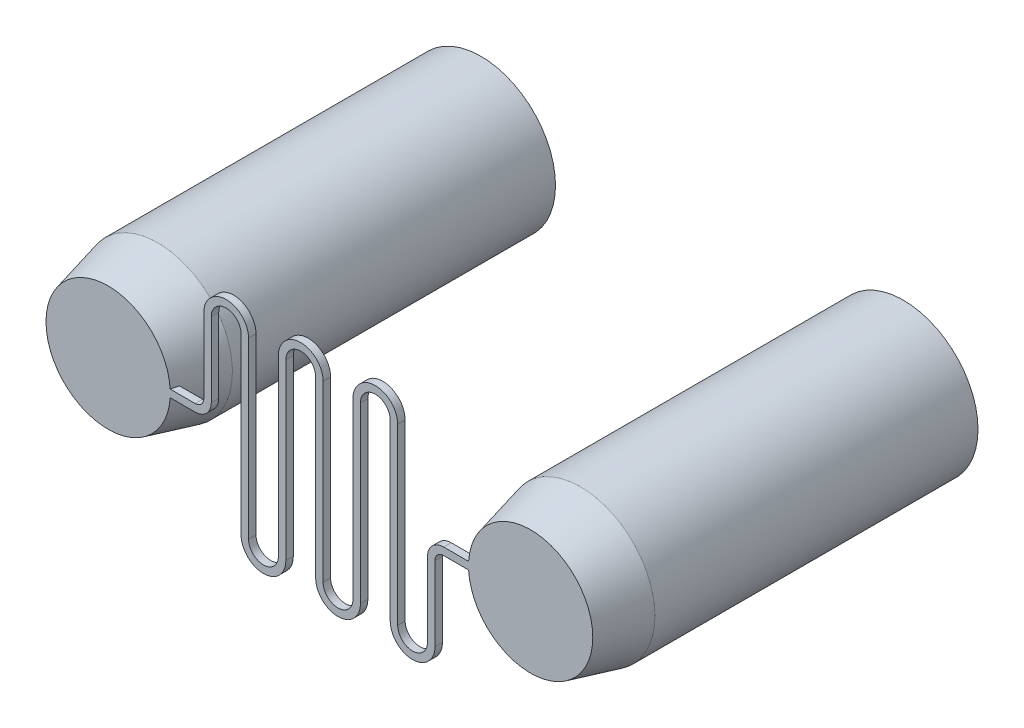
SolidWorks part; units mm, degrees
ref_plane "Front Plane" through (0, 0, 0) normal (0, 0, 1) x (1, 0, 0)
ref_plane "Top Plane" through (0, 0, 0) normal (0, 1, 0) x (1, 0, 0)
ref_plane "Right Plane" through (0, 0, 0) normal (1, 0, 0) x (0, 0, -1)
sketch "Sketch2" plane through (0, 0, 0) normal (0, 0, 1) x (1, 0, 0)
  line L3 (-20.5, -0.3) -> (-13.5, -0.3)
  line L6 (-12.2, 1) -> (-12.2, 7)
  line L9 (-9.8, 7) -> (-9.8, 0)
  line L12 (-9.8, 0) -> (-9.8, -7)
  line L15 (-6.2, -7) -> (-6.2, 0)
  line L18 (-6.2, 0) -> (-6.2, 7)
  line L21 (-3.8, 7) -> (-3.8, 0)
  line L22 (-3.8, 0) -> (-3.8, -7)
  line L23 (-0.2, -7) -> (-0.2, 0)
  line L24 (-0.2, 0) -> (-0.2, 7)
  line L25 (2.2, 7) -> (2.2, 0)
  line L26 (2.2, 0) -> (2.2, -7)
  line L27 (5.8, -7) -> (5.8, -1)
  line L28 (6.5, -0.3) -> (13.5, -0.3)
  line L29 (-20.5, 0.3) -> (-13.5, 0.3)
  line L30 (-12.8, 1) -> (-12.8, 7)
  line L31 (-9.2, 7) -> (-9.2, 0)
  line L32 (-9.2, 0) -> (-9.2, -7)
  line L33 (-6.8, -7) -> (-6.8, 0)
  line L34 (-6.8, 0) -> (-6.8, 7)
  line L35 (-3.2, 7) -> (-3.2, 0)
  line L36 (-3.2, 0) -> (-3.2, -7)
  line L37 (-0.8, -7) -> (-0.8, 0)
  line L38 (-0.8, 0) -> (-0.8, 7)
  line L39 (2.8, 7) -> (2.8, 0)
  line L40 (2.8, 0) -> (2.8, -7)
  line L41 (5.2, -7) -> (5.2, -1)
  line L42 (6.5, 0.3) -> (13.5, 0.3)
  arc A8 (-12.2, 1) -> (-13.5, -0.3) centre (-13.5, 1) cw
  arc A9 (-12.2, 7) -> (-9.8, 7) centre (-11, 7) cw
  arc A10 (-9.8, -7) -> (-6.2, -7) centre (-8, -7) ccw
  arc A11 (-6.2, 7) -> (-3.8, 7) centre (-5, 7) cw
  arc A12 (-3.8, -7) -> (-0.2, -7) centre (-2, -7) ccw
  arc A13 (-0.2, 7) -> (2.2, 7) centre (1, 7) cw
  arc A14 (2.2, -7) -> (5.8, -7) centre (4, -7) ccw
  arc A15 (5.8, -1) -> (6.5, -0.3) centre (6.5, -1) cw
  arc A16 (-12.8, 1) -> (-13.5, 0.3) centre (-13.5, 1) cw
  arc A17 (-12.8, 7) -> (-9.2, 7) centre (-11, 7) cw
  arc A18 (-9.2, -7) -> (-6.8, -7) centre (-8, -7) ccw
  arc A19 (-6.8, 7) -> (-3.2, 7) centre (-5, 7) cw
  arc A20 (-3.2, -7) -> (-0.8, -7) centre (-2, -7) ccw
  arc A21 (-0.8, 7) -> (2.8, 7) centre (1, 7) cw
  arc A22 (2.8, -7) -> (5.2, -7) centre (4, -7) ccw
  arc A23 (5.2, -1) -> (6.5, 0.3) centre (6.5, -1) cw
  arc A24 (-20.5, 0.3) -> (-20.5, -0.3) centre (-20.5, 0) ccw
  arc A25 (13.5, -0.3) -> (13.5, 0.3) centre (13.5, 0) ccw
  point P4 (0, 0)
  point P32 (5.5, 0)
  point P35 (-12.5, 0)
  dimension "D1" = 8
  dimension "D14" = 8
extrude "Boss-Extrude1" add sketch "Sketch2" along normal blind 0.6
ref_plane "Plane1" through (0, 0, 0) normal (0, 1, 0) x (1, 0, 0)
sketch "Sketch3" plane through (0, 0, 0) normal (0, 1, 0) x (1, 0, 0)
  line L0 (-20.5, -0.6) -> (-25.5, -0.6)
  line L2 (-20.5, -0.6) -> (-20.5, 29.4)
  line L3 (-20.5, 29.4) -> (-26.5, 29.4)
  line L4 (-26.5, 29.4) -> (-26.5, 3.4)
  line L5 (-26.5, 3.4) -> (-25.5, -0.6)
  dimension "D1" = 5
  dimension "D3" = 30
  dimension "D4" = 6
revolve "Revolve1" add sketch "Sketch3" angle 360 about L2
ref_plane "Plane2" through (0, 0, 0) normal (0, 1, 0) x (1, 0, 0)
sketch "Sketch4" plane through (0, 0, 0) normal (0, 1, 0) x (1, 0, 0)
  line L0 (13.5, -0.6) -> (18.5, -0.6)
  line L2 (13.5, -0.6) -> (13.5, 29.4)
  line L3 (13.5, 29.4) -> (19.5, 29.4)
  line L4 (19.5, 29.4) -> (19.5, 3.4)
  line L5 (19.5, 3.4) -> (18.5, -0.6)
  dimension "D1" = 5
  dimension "D3" = 30
  dimension "D4" = 6
revolve "Revolve2" add sketch "Sketch4" angle 360 about L2
sketch "Sketch5" plane through (0, 0, -29.4) normal (0, 0, -1) x (-1, 0, 0)
  circle A0 centre (-13.5, 0) radius 5
  circle A1 centre (20.5, 0) radius 5
  dimension "D1" = 10
  dimension "D2" = 10
extrude "Cut-Extrude1" cut sketch "Sketch5" against normal blind 27
